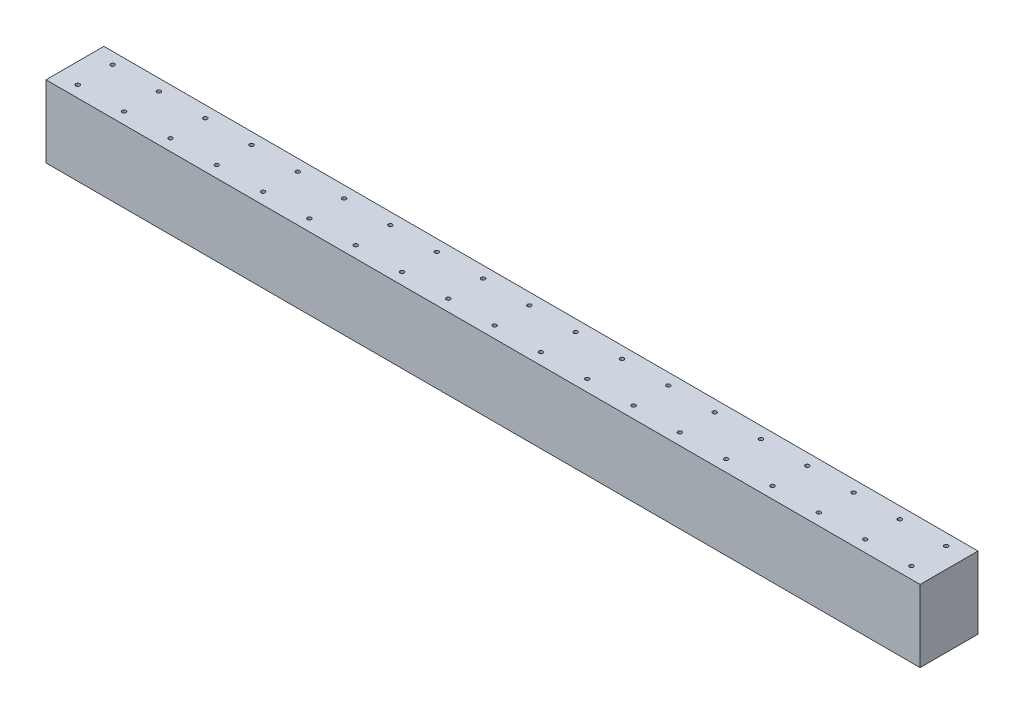
SolidWorks part; units mm, degrees
material "Plain Carbon Steel"
ref_plane "Front Plane" through (0, 0, 0) normal (0, 0, 1) x (1, 0, 0)
ref_plane "Top Plane" through (0, 0, 0) normal (0, 1, 0) x (1, 0, 0)
ref_plane "Right Plane" through (0, 0, 0) normal (1, 0, 0) x (0, 0, -1)
sketch "Sketch1" plane through (0, 0, 0) normal (0, 0, 1) x (1, 0, 0)
  line L0 (-755, 15) -> (755, 15)
  line L3 (755, 15) -> (755, 139.5)
  line L4 (0, 0) -> (0, 15) construction
  line L5 (-755, 15) -> (-755, 139.5)
  line L8 (-755, 139.5) -> (755, 139.5)
  line L9 (755, 15) -> (-755, 15) construction
  dimension "D1" = 124.5
  dimension "D4" = 1510
extrude "Boss-Extrude1" add sketch "Sketch1" against normal blind 100
ref_plane "Plane1" through (0, 0, -50) normal (0, 0, -1) x (-1, 0, 0)
hole_wizard "M8 Tapped Hole1" positions "Sketch4" profile "Sketch3" tap size "M8" standard "ISO"
sketch "Sketch4" plane through (0, 139.5, 0) normal (0, 1, 0) x (1, 0, 0)
  point P0 (720, 80)
  point P3 (720, 20)
  point P6 (640, 20)
  point P9 (640, 80)
  point P12 (560, 80)
  point P15 (560, 20)
  point P18 (480, 20)
  point P21 (480, 80)
  point P24 (400, 80)
  point P27 (400, 20)
  point P30 (320, 20)
  point P33 (320, 80)
  point P36 (240, 80)
  point P39 (240, 20)
  point P42 (160, 20)
  point P45 (160, 80)
  point P48 (80, 80)
  point P51 (80, 20)
  point P54 (0, 20)
  point P57 (0, 80)
  point P60 (-80, 80)
  point P63 (-80, 20)
  point P66 (-160, 20)
  point P69 (-160, 80)
  point P72 (-240, 80)
  point P75 (-240, 20)
  point P78 (-320, 20)
  point P81 (-320, 80)
  point P84 (-400, 80)
  point P87 (-400, 20)
  point P90 (-480, 20)
  point P93 (-480, 80)
  point P96 (-560, 20)
  point P99 (-560, 80)
  point P102 (-640, 20)
  point P105 (-640, 80)
  point P108 (-720, 80)
  point P111 (-720, 20)
sketch "Sketch3" plane through (720, 139.5, -80) normal (1, 0, 0) x (0, 0, 1)
  line L0 (0, 0) -> (0, 24.2929)
  line L1 (0, 24.2929) -> (3.4, 22.25)
  line L2 (3.4, 22.25) -> (3.4, 0)
  line L5 (3.4, 0) -> (0, 0)
  line L10 (0, 24.2929) -> (-3.4, 22.25) construction
  line L11 (0, -6.35) -> (0, 107.95) construction
  dimension "Tap Drill Dia." = 6.8
  dimension "Tap Drill Depth" = 22.25
  dimension "Drill Angle" = 118
cosmetic thread "Hole Thread1"
cosmetic thread "Hole Thread2"
cosmetic thread "Hole Thread3"
cosmetic thread "Hole Thread4"
cosmetic thread "Hole Thread5"
cosmetic thread "Hole Thread6"
cosmetic thread "Hole Thread7"
cosmetic thread "Hole Thread8"
cosmetic thread "Hole Thread9"
cosmetic thread "Hole Thread10"
cosmetic thread "Hole Thread11"
cosmetic thread "Hole Thread12"
cosmetic thread "Hole Thread13"
cosmetic thread "Hole Thread14"
cosmetic thread "Hole Thread15"
cosmetic thread "Hole Thread16"
cosmetic thread "Hole Thread17"
cosmetic thread "Hole Thread18"
cosmetic thread "Hole Thread19"
cosmetic thread "Hole Thread20"
cosmetic thread "Hole Thread21"
cosmetic thread "Hole Thread22"
cosmetic thread "Hole Thread23"
cosmetic thread "Hole Thread24"
cosmetic thread "Hole Thread25"
cosmetic thread "Hole Thread26"
cosmetic thread "Hole Thread27"
cosmetic thread "Hole Thread28"
cosmetic thread "Hole Thread29"
cosmetic thread "Hole Thread30"
cosmetic thread "Hole Thread31"
cosmetic thread "Hole Thread32"
cosmetic thread "Hole Thread33"
cosmetic thread "Hole Thread34"
cosmetic thread "Hole Thread35"
cosmetic thread "Hole Thread36"
cosmetic thread "Hole Thread37"
cosmetic thread "Hole Thread38"
